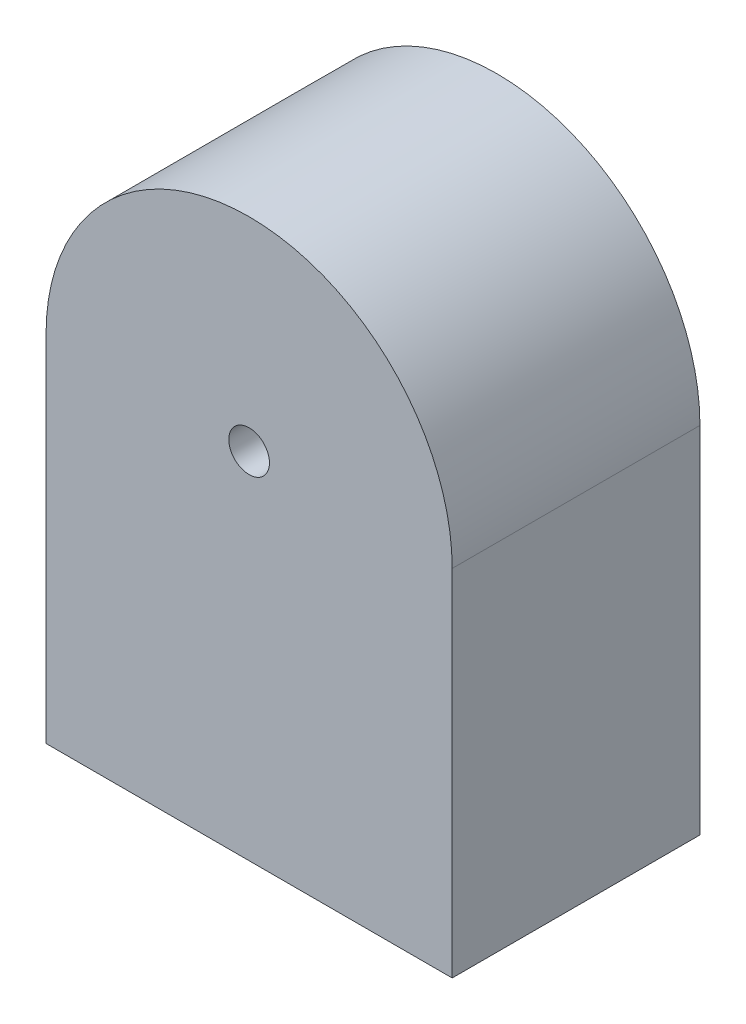
SolidWorks part; units mm, degrees
material "CA"
ref_plane "Plan de face" through (0, 0, 0) normal (0, 0, 1) x (1, 0, 0)
ref_plane "Plan de dessus" through (0, 0, 0) normal (0, 1, 0) x (1, 0, 0)
ref_plane "Plan de droite" through (0, 0, 0) normal (1, 0, 0) x (0, 0, -1)
sketch "Esquisse2" plane through (0, 0, 0) normal (0, 0, 1) x (1, 0, 0)
  line L0 (0, 0) -> (30, 0)
  line L1 (30, 0) -> (30, 26.2)
  line L2 (0, 0) -> (0, 26.2)
  arc A0 (0, 26.2) -> (30, 26.2) centre (15, 26.2) cw
  circle A1 centre (15, 26.2) radius 1.5
  dimension "D1" = 26.2
  dimension "D2" = 30
extrude "Boss.-Extru.2" add sketch "Esquisse2" along normal blind 18.3
sketch "Esquisse7" plane through (0, 0, 0) normal (1, 0, 0) x (0, 0, -1)
  line L0 (-7.0374, 3.4069) -> (-7.0374, 45.4797) construction
  text T0 "Maxon 110512\r\nHEDL5540"
extrude "Boss.-Extru.3" add sketch "Esquisse7" along normal blind 10 separate body
split line "Ligne de séparation1"
delete or keep bodies "Corps-Effacer/suppr1" type delete bodies bodies 102 103 104 105 106 107 108 109 110 111 112 113 114 115 116 117 118 119 120
